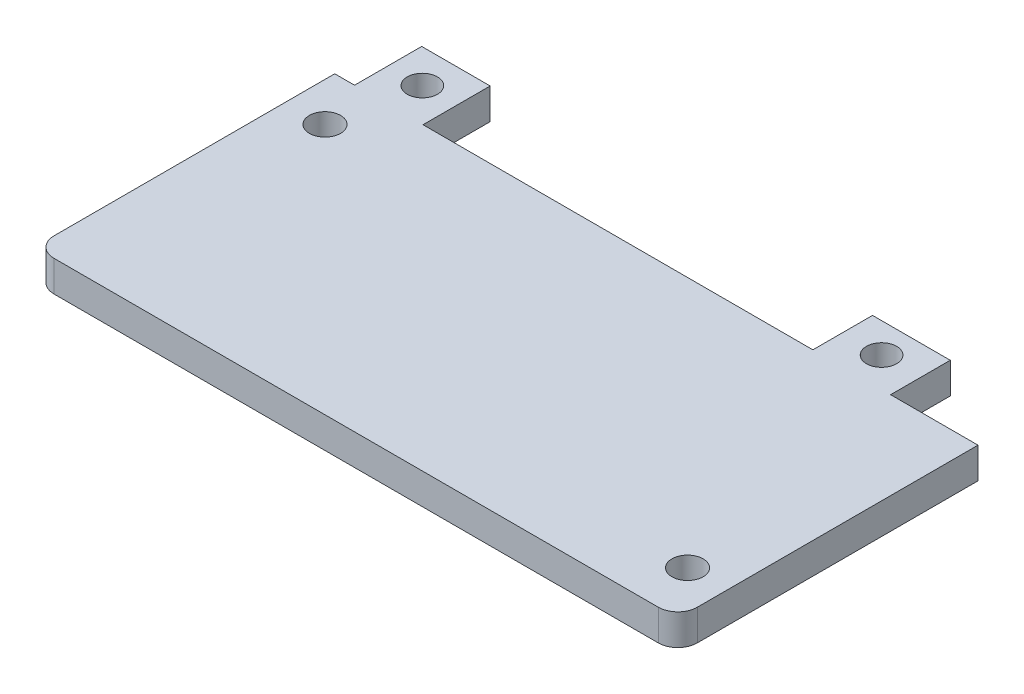
SolidWorks part; units mm, degrees
ref_plane "Front Plane" through (0, 0, 0) normal (0, 0, 1) x (1, 0, 0)
ref_plane "Top Plane" through (0, 0, 0) normal (0, 1, 0) x (1, 0, 0)
ref_plane "Right Plane" through (0, 0, 0) normal (1, 0, 0) x (0, 0, -1)
sketch "Sketch2" plane through (0, 0, 0) normal (0, 1, 0) x (1, 0, 0)
  line L0 (9.0586, 30.8) -> (9.0586, 37.6894)
  line L1 (0, 0) -> (66, 0)
  line L2 (0, 0) -> (0, 30.8)
  line L3 (9.0586, 30.8) -> (49.0586, 30.8)
  line L4 (66, 0) -> (66, 30.8)
  line L14 (2.0334, 37.6894) -> (2.0334, 30.8)
  line L16 (49.0586, 30.8) -> (49.0586, 36.9203)
  line L17 (49.0586, 36.9203) -> (57.0334, 36.9203)
  line L23 (2.0334, 110.8) -> (2.0334, 30.8) construction
  line L24 (2.0334, 30.8) -> (0, 30.8)
  line L25 (57.0334, 30.8) -> (57.0334, 36.9203)
  line L26 (57.0334, 30.8) -> (57.0334, 110.8) construction
  line L27 (66, 30.8) -> (0, 30.8) construction
  line L28 (57.0334, 30.8) -> (66, 30.8)
  line L29 (2.0334, 37.6894) -> (9.0586, 37.6894)
  circle A0 centre (62, 5) radius 1.6
  circle A1 centre (4, 25.8) radius 1.6
  circle A2 centre (5.546, 34.2447) radius 1.55
  circle A3 centre (53.046, 33.8601) radius 1.55
  point P9 (2.0334, 34.2447)
  point P28 (57.0334, 33.8601)
  point P29 (5.546, 37.6894)
  point P30 (53.046, 36.9203)
  dimension "D2" = 3.2
  dimension "D8" = 3.1
  dimension "D9" = 3.1
  dimension "D1" = 66
  dimension "D3" = 4
  dimension "D4" = 5
  dimension "D5" = 4
  dimension "D6" = 25.8
  dimension "D7" = 30.8
extrude "Boss-Extrude1" add sketch "Sketch2" along normal blind 3.175
fillet "Fillet1" radius 2 2 edges at (66, 1.5875, 0) (0, 1.5875, 0)
equation "\"D9@Sketch2\"=\"D8@Sketch2\""
